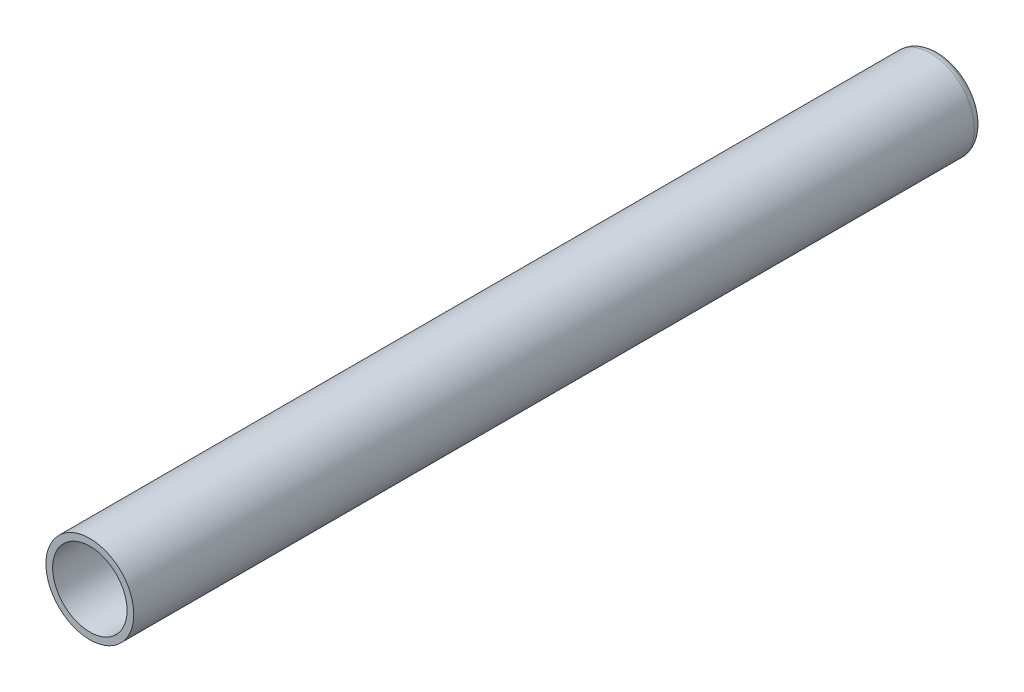
SolidWorks part; units mm, degrees
ref_plane "Alzado" through (0, 0, 0) normal (0, 0, 1) x (1, 0, 0)
ref_plane "Planta" through (0, 0, 0) normal (0, 1, 0) x (1, 0, 0)
ref_plane "Vista lateral" through (0, 0, 0) normal (1, 0, 0) x (0, 0, -1)
sketch "Croquis2" plane through (0, 0, 0) normal (0, 0, 1) x (1, 0, 0)
  circle A0 centre (0, 0) radius 15
  dimension "D1" = 30
extrude "Saliente-Extruir1" add sketch "Croquis2" against normal blind 290
sketch "Croquis3" plane through (0, 0, 0) normal (0, 0, 1) x (1, 0, 0)
  circle A0 centre (0, 0) radius 12.7
  dimension "D1" = 25.4
extrude "Cortar-Extruir1" cut sketch "Croquis3" against normal blind 282
fillet "Redondeo1" radius 3 1 edges at (15, 0, -290)
